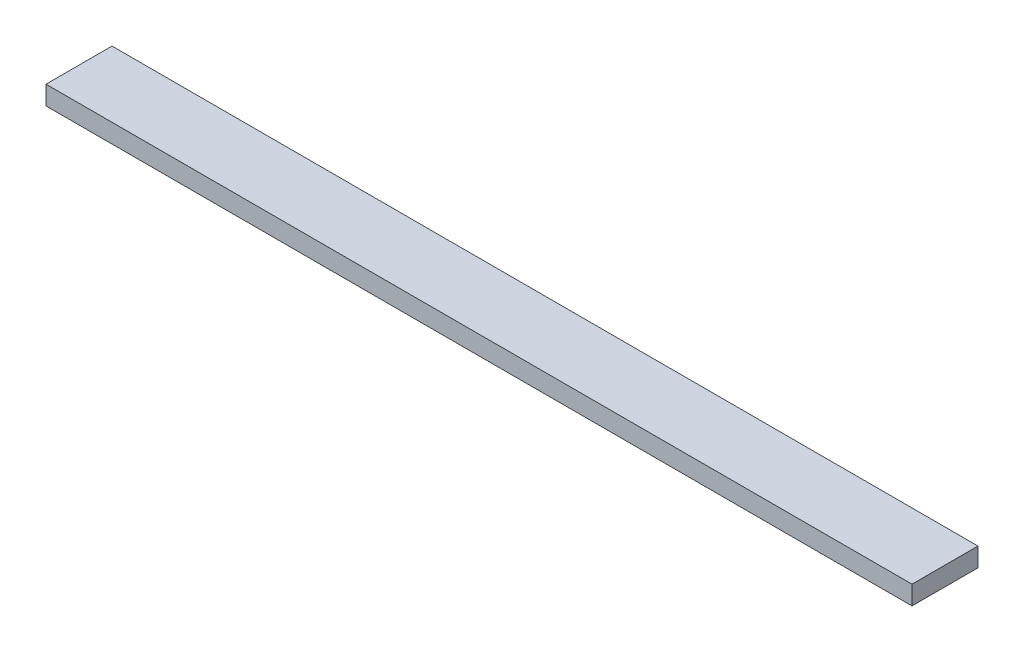
SolidWorks part; units mm, degrees
ref_plane "Front Plane" through (0, 0, 0) normal (0, 0, 1) x (1, 0, 0)
ref_plane "Top Plane" through (0, 0, 0) normal (0, 1, 0) x (1, 0, 0)
ref_plane "Right Plane" through (0, 0, 0) normal (1, 0, 0) x (0, 0, -1)
sketch "Sketch1" plane through (0, 0, 0) normal (0, 1, 0) x (1, 0, 0)
  line L1 (-91.8333, -7) -> (91.8333, -7)
  line L2 (-91.8333, -7) -> (-91.8333, 7)
  line L3 (-91.8333, 7) -> (91.8333, 7)
  line L4 (91.8333, -7) -> (91.8333, 7)
  line L5 (-91.8333, -7) -> (91.8333, 7) construction
  line L6 (-91.8333, 7) -> (91.8333, -7) construction
  point P0 (0, 0)
  dimension "D1" = 183.6667
  dimension "D2" = 14
extrude "Boss-Extrude1" add sketch "Sketch1" along normal blind 4
equation "\"D1@Sketch1\"=(551mm/3)"
